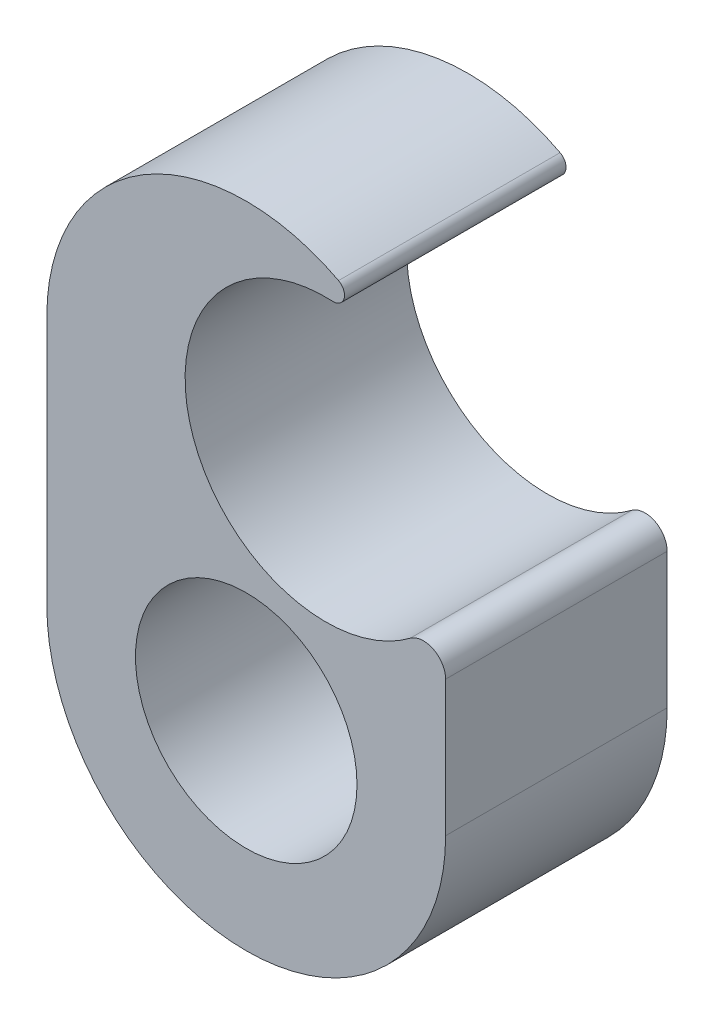
SolidWorks part; units mm, degrees
ref_plane "Front Plane" through (0, 0, 0) normal (0, 0, 1) x (1, 0, 0)
ref_plane "Top Plane" through (0, 0, 0) normal (0, 1, 0) x (1, 0, 0)
ref_plane "Right Plane" through (0, 0, 0) normal (1, 0, 0) x (0, 0, -1)
sketch "Sketch1" plane through (0, 0, 0) normal (0, 0, 1) x (1, 0, 0)
  line L2 (0, 0) -> (0, 11.3076)
  line L4 (18, 0) -> (18, 6.1192)
  arc A0 (0, 11.3076) -> (13.1677, 19.2845) centre (9, 11.3076) cw
  arc A1 (18, 0) -> (0, 0) centre (9, 0) cw
  circle A2 centre (9, 0) radius 5
  arc A4 (12.911, 18.3419) -> (16.4001, 6.9193) centre (12.591, 12) ccw
  arc A5 (18, 6.1192) -> (16.4001, 6.9193) centre (17, 6.1192) ccw
  arc A6 (13.1677, 19.2845) -> (12.911, 18.3419) centre (12.9362, 18.8413) cw
  dimension "D1" = 10
  dimension "D2" = 12.7
  dimension "D4" = 1
  dimension "D6" = 0.5
  dimension "D3" = 12
  dimension "D5" = 18
extrude "Boss-Extrude1" add sketch "Sketch1" along normal blind 10
